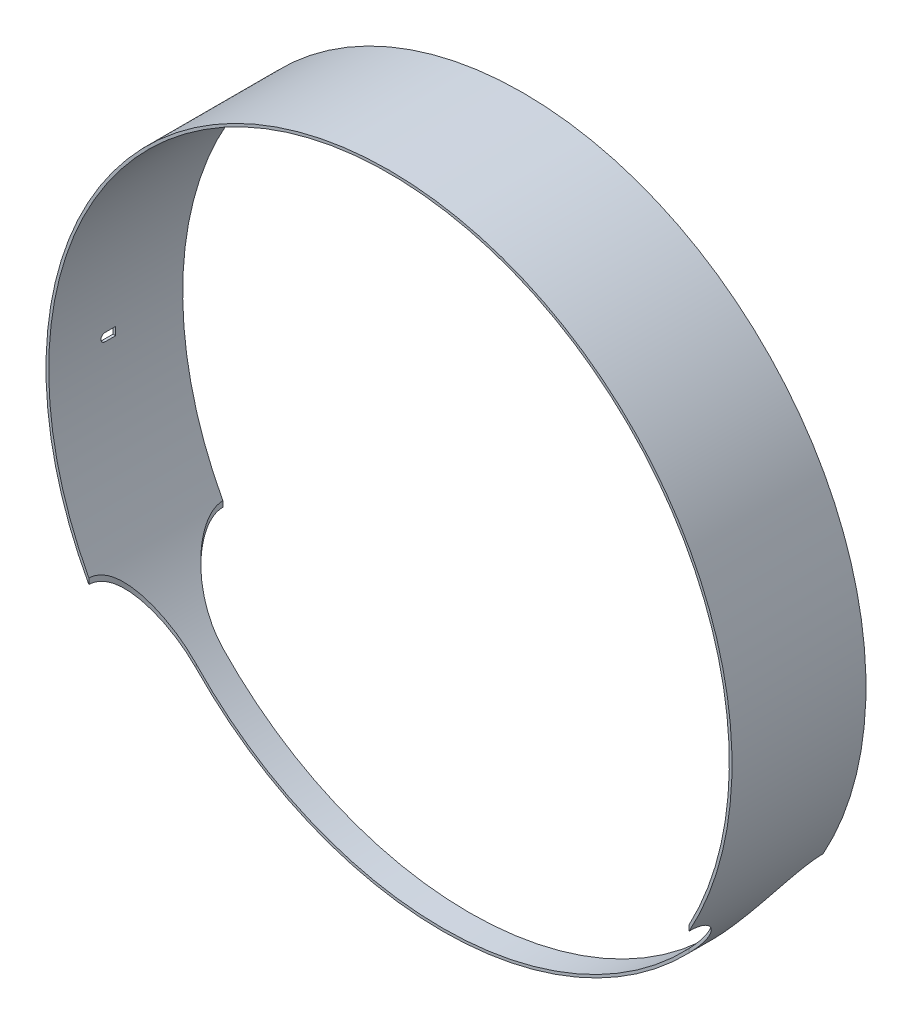
SolidWorks part; units mm, degrees
ref_plane "前视基准面" through (0, 0, 0) normal (0, 0, 1) x (1, 0, 0)
ref_plane "上视基准面" through (0, 0, 0) normal (0, 1, 0) x (1, 0, 0)
ref_plane "右视基准面" through (0, 0, 0) normal (1, 0, 0) x (0, 0, -1)
sketch "草图3" plane through (0, 0, 0) normal (0, 0, 1) x (1, 0, 0)
  circle A0 centre (0, 0) radius 64
  circle A1 centre (0, 0) radius 63.5
  dimension "D1" = 128
  dimension "D2" = 127
extrude "凸台-拉伸2" add sketch "草图3" along normal blind 25
sketch "草图4" plane through (0, 0, 0) normal (0, 1, 0) x (1, 0, 0)
  line L1 (63.5, 0) -> (-63.5, 0) construction
  line L3 (64, 0) -> (-64, 0) construction
  line L5 (-46, -10) -> (46, -10)
  line L7 (0, -55) -> (0, 55) construction
  line L10 (-56, 0) -> (56, 0)
  line L11 (-64, -12.5) -> (64, -12.5) construction
  line L12 (-64, 0) -> (-64, -25) construction
  line L13 (64, -25) -> (64, 0) construction
  line L14 (-46, -15) -> (46, -15)
  line L15 (-56, -25) -> (56, -25)
  arc A0 (-56, 0) -> (-46, -10) centre (-46, 0) ccw
  arc A2 (56, 0) -> (46, -10) centre (46, 0) cw
  arc A3 (-56, -25) -> (-46, -15) centre (-46, -25) cw
  arc A4 (56, -25) -> (46, -15) centre (46, -25) ccw
  dimension "D6" = 10
extrude "切除-拉伸2" cut sketch "草图4" against normal blind 200
sketch "草图6" plane through (0, 0, 0) normal (1, 0, 0) x (0, 0, -1)
  line L2 (-12.5, -0.75) -> (-12.5, 0.75)
  line L4 (-25, 64) -> (-25, -30.9839) construction
  line L5 (-12.5, 0.75) -> (-12.5, 2.648) construction
  line L6 (-14.5, 0.75) -> (-12.5, 0.75)
  line L7 (-14.5, -0.75) -> (-12.5, -0.75)
  arc A1 (-14.5, 0.75) -> (-14.5, -0.75) centre (-14.5, 0) ccw
  dimension "D4" = 12.5
extrude "切除-拉伸3" cut sketch "草图6" against normal blind 200
